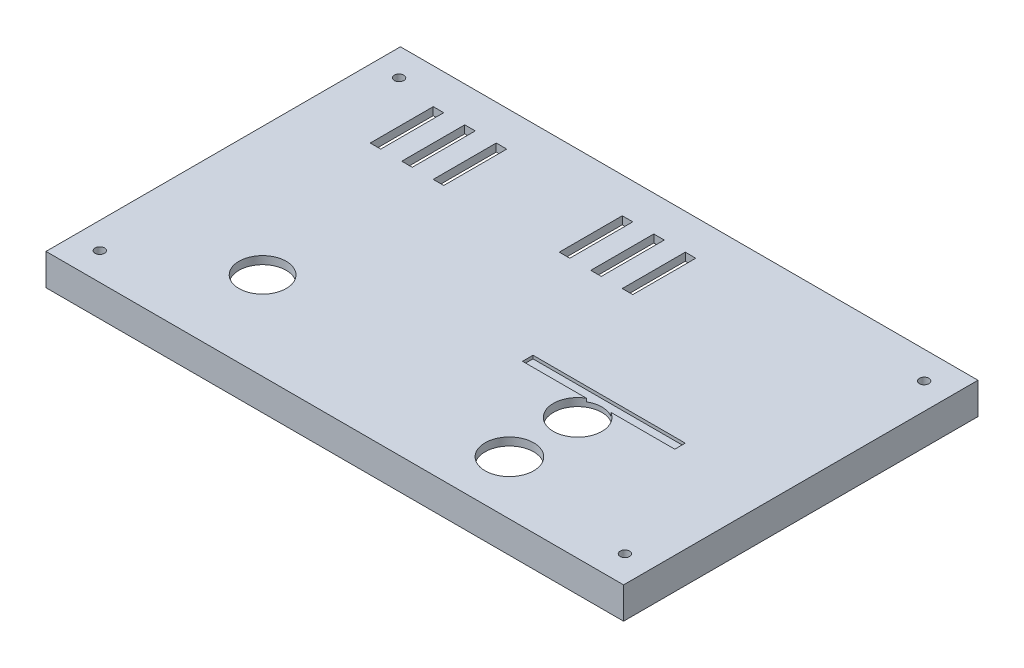
SolidWorks part; units mm, degrees
ref_plane "前视基准面" through (0, 0, 0) normal (0, 0, 1) x (1, 0, 0)
ref_plane "上视基准面" through (0, 0, 0) normal (0, 1, 0) x (1, 0, 0)
ref_plane "右视基准面" through (0, 0, 0) normal (1, 0, 0) x (0, 0, -1)
other "Configuration Table"
sketch "草图1" plane through (0, 0, 0) normal (0, 1, 0) x (1, 0, 0)
  line L1 (-110, -67.5) -> (110, -67.5)
  line L2 (-110, -67.5) -> (-110, 67.5)
  line L3 (-110, 67.5) -> (110, 67.5)
  line L4 (110, -67.5) -> (110, 67.5)
extrude "Lid_Top_3mm" add sketch "草图1" against normal blind 3
sketch "草图2" plane through (0, 0, 0) normal (0, 1, 0) x (1, 0, 0)
  line L0 (110, 67.5) -> (-110, 67.5) construction
  line L1 (-108, 65.5) -> (108, 65.5)
  line L2 (-108, 65.5) -> (-108, 67.5)
  line L3 (-108, 67.5) -> (108, 67.5)
  line L4 (108, 65.5) -> (108, 67.5)
extrude "Lid_Rim_Back" add sketch "草图2" against normal blind 12
sketch "草图3" plane through (0, 0, 0) normal (0, 1, 0) x (1, 0, 0)
  line L0 (-110, -67.5) -> (110, -67.5) construction
  line L1 (-108, -67.5) -> (108, -67.5)
  line L2 (-108, -67.5) -> (-108, -65.5)
  line L3 (-108, -65.5) -> (108, -65.5)
  line L4 (108, -67.5) -> (108, -65.5)
extrude "Lid_Rim_Front" add sketch "草图3" against normal blind 12
sketch "草图4" plane through (0, 0, 0) normal (0, 1, 0) x (1, 0, 0)
  line L1 (-110, -67.5) -> (-108, -67.5)
  line L2 (-110, -67.5) -> (-110, 67.5)
  line L3 (-110, 67.5) -> (-108, 67.5)
  line L4 (-108, -67.5) -> (-108, 67.5)
extrude "Lid_Rim_Left" add sketch "草图4" against normal blind 12
sketch "草图5" plane through (0, 0, 0) normal (0, 1, 0) x (1, 0, 0)
  line L0 (-110, -67.5) -> (110, -67.5) construction
  line L1 (108, -67.5) -> (110, -67.5)
  line L2 (108, -67.5) -> (108, 67.5)
  line L3 (108, 67.5) -> (110, 67.5)
  line L4 (110, -67.5) -> (110, 67.5)
extrude "Lid_Rim_Right" add sketch "草图5" against normal blind 12
sketch "草图6" plane through (0, 0, 0) normal (0, 1, 0) x (1, 0, 0)
  circle A0 centre (-100, -57) radius 1.8
extrude "Lid_Screw_Clearance_1" cut sketch "草图6" against normal blind 16
sketch "草图7" plane through (0, 0, 0) normal (0, 1, 0) x (1, 0, 0)
  circle A0 centre (100, -57) radius 1.8
extrude "Lid_Screw_Clearance_2" cut sketch "草图7" against normal blind 16
sketch "草图8" plane through (0, 0, 0) normal (0, 1, 0) x (1, 0, 0)
  circle A0 centre (-100, 57) radius 1.8
extrude "Lid_Screw_Clearance_3" cut sketch "草图8" against normal blind 16
sketch "草图9" plane through (0, 0, 0) normal (0, 1, 0) x (1, 0, 0)
  circle A0 centre (100, 57) radius 1.8
extrude "Lid_Screw_Clearance_4" cut sketch "草图9" against normal blind 16
sketch "草图10" plane through (0, 0, 0) normal (0, 1, 0) x (1, 0, 0)
  circle A0 centre (-61, -34) radius 9
extrude "OV5647_Lens_Opening_D18" cut sketch "草图10" against normal blind 4
sketch "草图11" plane through (0, 0, 0) normal (0, 1, 0) x (1, 0, 0)
  circle A0 centre (46, -47) radius 9.25
extrude "HC_SR04_Acoustic_Opening_1" cut sketch "草图11" against normal blind 4
sketch "草图12" plane through (0, 0, 0) normal (0, 1, 0) x (1, 0, 0)
  circle A0 centre (46, -21) radius 9.25
extrude "HC_SR04_Acoustic_Opening_2" cut sketch "草图12" against normal blind 4
sketch "草图13" plane through (0, 0, 0) normal (0, 1, 0) x (1, 0, 0)
  line L1 (17, -13) -> (75, -13)
  line L2 (17, -13) -> (17, -9)
  line L3 (17, -9) -> (75, -9)
  line L4 (75, -13) -> (75, -9)
extrude "HC_SR04_Alignment_Recess" cut sketch "草图13" against normal blind 1.2
sketch "草图14" plane through (0, 0, 0) normal (0, 1, 0) x (1, 0, 0)
  line L1 (-84, 30) -> (-80, 30)
  line L2 (-84, 30) -> (-84, 54)
  line L3 (-84, 54) -> (-80, 54)
  line L4 (-80, 30) -> (-80, 54)
extrude "Vent_Slot_1" cut sketch "草图14" against normal blind 4
sketch "草图15" plane through (0, 0, 0) normal (0, 1, 0) x (1, 0, 0)
  line L1 (-72, 30) -> (-68, 30)
  line L2 (-72, 30) -> (-72, 54)
  line L3 (-72, 54) -> (-68, 54)
  line L4 (-68, 30) -> (-68, 54)
extrude "Vent_Slot_2" cut sketch "草图15" against normal blind 4
sketch "草图16" plane through (0, 0, 0) normal (0, 1, 0) x (1, 0, 0)
  line L1 (-60, 30) -> (-56, 30)
  line L2 (-60, 30) -> (-60, 54)
  line L3 (-60, 54) -> (-56, 54)
  line L4 (-56, 30) -> (-56, 54)
extrude "Vent_Slot_3" cut sketch "草图16" against normal blind 4
sketch "草图17" plane through (0, 0, 0) normal (0, 1, 0) x (1, 0, 0)
  line L1 (-12, 30) -> (-8, 30)
  line L2 (-12, 30) -> (-12, 54)
  line L3 (-12, 54) -> (-8, 54)
  line L4 (-8, 30) -> (-8, 54)
extrude "Vent_Slot_4" cut sketch "草图17" against normal blind 4
sketch "草图18" plane through (0, 0, 0) normal (0, 1, 0) x (1, 0, 0)
  line L1 (0, 30) -> (4, 30)
  line L2 (0, 30) -> (0, 54)
  line L3 (0, 54) -> (4, 54)
  line L4 (4, 30) -> (4, 54)
extrude "Vent_Slot_5" cut sketch "草图18" against normal blind 4
sketch "草图19" plane through (0, 0, 0) normal (0, 1, 0) x (1, 0, 0)
  line L1 (12, 30) -> (16, 30)
  line L2 (12, 30) -> (12, 54)
  line L3 (12, 54) -> (16, 54)
  line L4 (16, 30) -> (16, 54)
extrude "Vent_Slot_6" cut sketch "草图19" against normal blind 4
